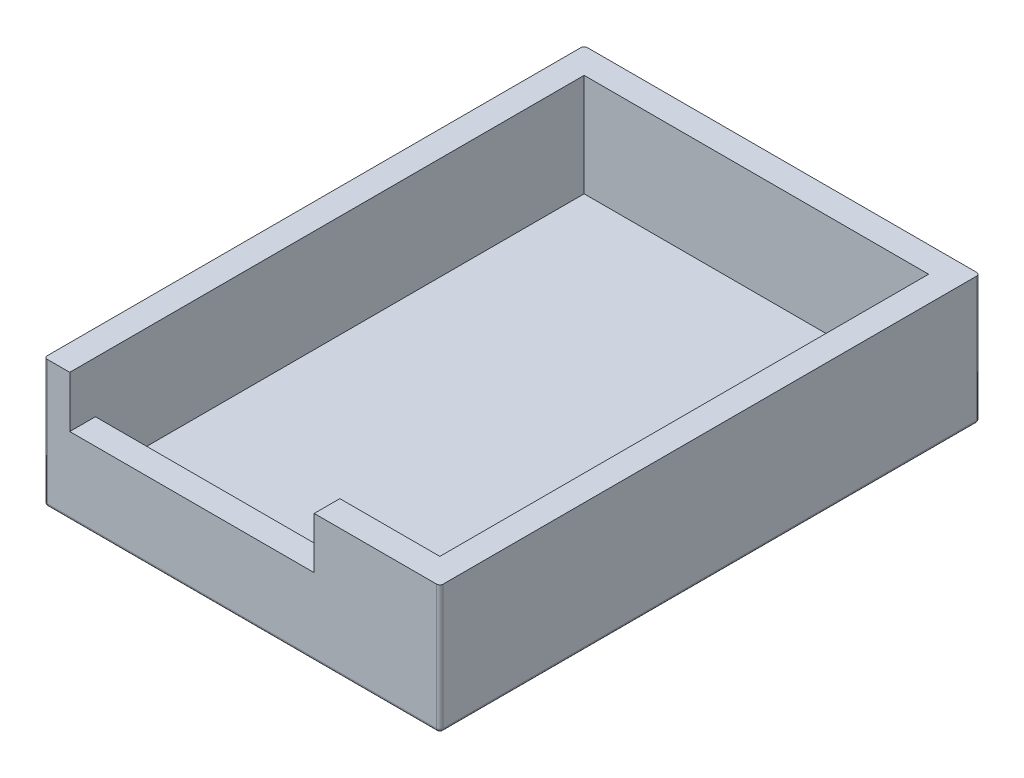
SolidWorks part; units mm, degrees
ref_plane "Front Plane" through (0, 0, 0) normal (0, 0, 1) x (1, 0, 0)
ref_plane "Top Plane" through (0, 0, 0) normal (0, 1, 0) x (1, 0, 0)
ref_plane "Right Plane" through (0, 0, 0) normal (1, 0, 0) x (0, 0, -1)
sketch "Sketch1" plane through (0, 0, 0) normal (0, 1, 0) x (1, 0, 0)
  line L1 (-15.43, -21.055) -> (15.43, -21.055)
  line L2 (-15.43, -21.055) -> (-15.43, 21.055)
  line L3 (-15.43, 21.055) -> (15.43, 21.055)
  line L4 (15.43, -21.055) -> (15.43, 21.055)
  line L5 (-15.43, -21.055) -> (15.43, 21.055) construction
  line L6 (-15.43, 21.055) -> (15.43, -21.055) construction
  point P0 (0, 0)
  dimension "D1" = 30.86
  dimension "D2" = 42.11
extrude "Boss-Extrude1" add sketch "Sketch1" along normal blind 10
shell "Shell2" thickness 2
sketch "Sketch4" plane through (0, 10, 0) normal (0, 1, 0) x (1, 0, 0)
  line L0 (-15.43, -21.055) -> (15.43, -21.055) construction
  line L1 (-13.43, -19.055) -> (5.63, -19.055)
  line L2 (-13.43, -19.055) -> (-13.43, -21.055)
  line L3 (-13.43, -21.055) -> (5.63, -21.055)
  line L4 (5.63, -19.055) -> (5.63, -21.055)
  dimension "D1" = 19.06
extrude "Cut-Extrude1" cut sketch "Sketch4" against normal blind 4
fillet "Fillet1" radius 0.25 8 edges at (0, 0, -21.055) (-15.43, 0, 0) (-15.43, 5, -21.055) (15.43, 5, -21.055) (-15.43, 5, 21.055) (15.43, 0, 0) (15.43, 5, 21.055) (0, 0, 21.055)
sketch "Sketch5" plane through (0, 0, 0) normal (0, -1, 0) x (1, 0, 0)
  circle A0 centre (3.9555, 15.6468) radius 1.5
  dimension "D1" = 3
extrude "Cut-Extrude2" cut sketch "Sketch5" against normal through all
sketch "Sketch6" plane through (0, 0, 0) normal (0, -1, 0) x (1, 0, 0)
  circle A0 centre (8.5786, 12.7258) radius 1.5
  dimension "D1" = 3
extrude "Cut-Extrude3" cut sketch "Sketch6" against normal through all
